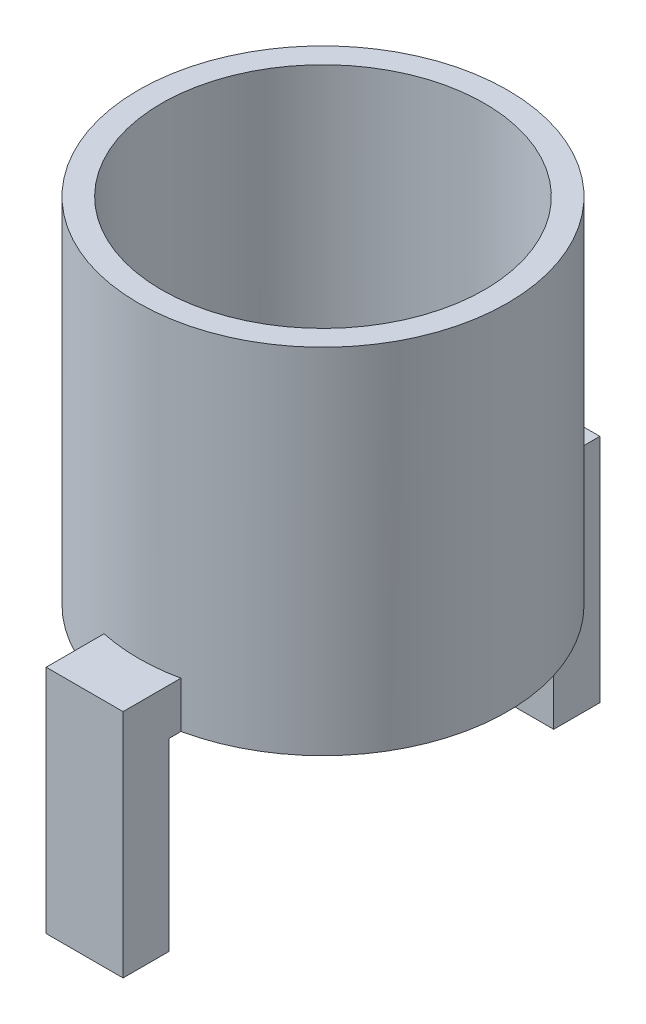
SolidWorks part; units mm, degrees
ref_plane "Front Plane" through (0, 0, 0) normal (0, 0, 1) x (1, 0, 0)
ref_plane "Top Plane" through (0, 0, 0) normal (0, 1, 0) x (1, 0, 0)
ref_plane "Right Plane" through (0, 0, 0) normal (1, 0, 0) x (0, 0, -1)
sketch "Sketch1" plane through (0, 0, 0) normal (0, 1, 0) x (1, 0, 0)
  line L0 (0, -14) -> (0, 14) construction
  line L2 (2.5, -15.5) -> (-2.5, -15.5)
  line L3 (2.5, -15.5) -> (2.5, -12.5)
  line L4 (2.5, -12.5) -> (-2.5, -12.5)
  line L5 (-2.5, -15.5) -> (-2.5, -12.5)
  line L6 (2.5, -15.5) -> (-2.5, -12.5) construction
  line L7 (2.5, -12.5) -> (-2.5, -15.5) construction
  line L8 (-2.5, 12.5) -> (2.5, 12.5)
  line L9 (-2.5, 12.5) -> (-2.5, 15.5)
  line L10 (-2.5, 15.5) -> (2.5, 15.5)
  line L11 (2.5, 12.5) -> (2.5, 15.5)
  line L12 (-2.5, 12.5) -> (2.5, 15.5) construction
  line L13 (-2.5, 15.5) -> (2.5, 12.5) construction
  point P4 (0, 0)
  dimension "D1" = 5
  dimension "D2" = 3
  dimension "D3" = 5
  dimension "D4" = 3
extrude "Boss-Extrude1" add sketch "Sketch1" along normal blind 15
sketch "Sketch2" plane through (0, 15, 0) normal (0, 1, 0) x (1, 0, 0)
  circle A0 centre (0, 0) radius 12
extrude "Boss-Extrude2" add sketch "Sketch2" along normal blind 20 and the other way blind 3
sketch "Sketch4" plane through (0, 0, -12.5) normal (0, 0, 1) x (1, 0, 0)
  line L0 (2.5, 15) -> (2.5, 0) construction
  line L1 (-2.5, 15) -> (2.5, 15)
  line L2 (-2.5, 15) -> (-2.5, 11.9952)
  line L3 (-2.5, 11.9952) -> (2.5, 11.9952)
  line L4 (2.5, 15) -> (2.5, 11.9952)
  line L5 (-2.5, 15) -> (2.5, 11.9952) construction
  line L6 (-2.5, 11.9952) -> (2.5, 15) construction
  point P4 (0, 13.4976)
extrude "Boss-Extrude3" add sketch "Sketch4" along normal blind 28
sketch "Sketch3" plane through (0, 35, 0) normal (0, 1, 0) x (1, 0, 0)
  circle A3 centre (0, 0) radius 10.5
  circle A4 centre (0, 0) radius 10.5
  dimension "D1" = 1.5
extrude "Cut-Extrude1" cut sketch "Sketch3" against normal blind 25
